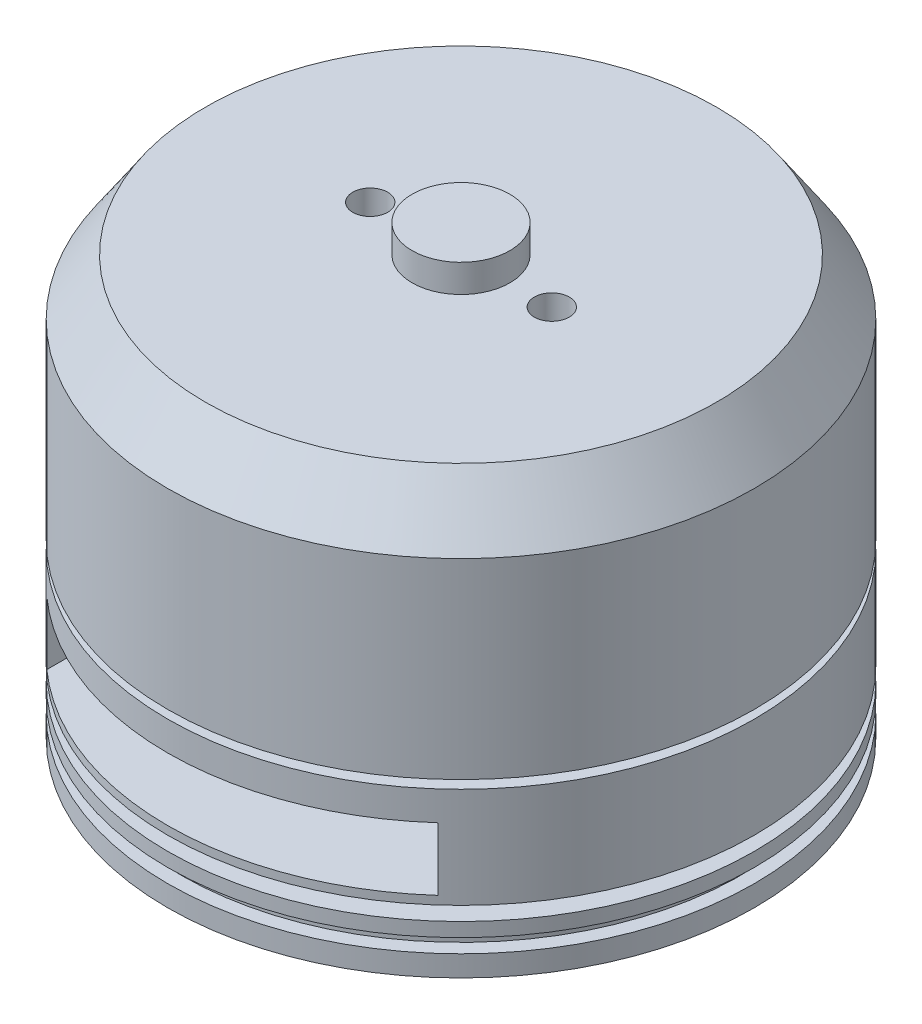
SolidWorks part; units mm, degrees
ref_plane "前视基准面" through (0, 0, 0) normal (0, 0, 1) x (1, 0, 0)
ref_plane "上视基准面" through (0, 0, 0) normal (0, 1, 0) x (1, 0, 0)
ref_plane "右视基准面" through (0, 0, 0) normal (1, 0, 0) x (0, 0, -1)
sketch "草图1" plane through (0, 0, 0) normal (0, 0, 1) x (1, 0, 0)
  line L0 (0, 0) -> (4.1, 0)
  line L1 (4.1, 0) -> (4.1, 6.7)
  line L2 (4.1, 6.7) -> (13.4, 6.7)
  line L3 (13.4, 6.7) -> (13.4, 8.7)
  line L4 (13.4, 8.7) -> (21, 8.7)
  line L5 (21, 8.7) -> (21, 10.2)
  line L6 (21, 10.2) -> (20, 10.2)
  line L7 (20, 10.2) -> (20, 11.2)
  line L8 (20, 11.2) -> (21, 11.2)
  line L9 (21, 11.2) -> (21, 12.2)
  line L10 (21, 12.2) -> (10, 12.2)
  line L11 (10, 12.2) -> (10, 13.2)
  line L12 (10, 13.2) -> (21, 13.2)
  line L13 (21, 13.2) -> (21, 20.4)
  line L14 (21, 20.4) -> (5, 20.4)
  line L15 (5, 20.4) -> (5, 21)
  line L16 (5, 21) -> (21, 21)
  line L17 (21, 21) -> (21, 34.7)
  line L18 (21, 34.7) -> (18.3, 38.7)
  line L19 (18.3, 38.7) -> (3.5, 38.7)
  line L20 (3.5, 38.7) -> (3.5, 43.7)
  line L21 (3.5, 43.7) -> (0, 43.7)
  line L22 (0, 43.7) -> (0, 0) construction
  line L23 (0, 0) -> (0, 43.7)
  dimension "D1" = 8.2
  dimension "D2" = 26.8
  dimension "D3" = 42
  dimension "D4" = 10
  dimension "D5" = 1.5
  dimension "D6" = 1
  dimension "D7" = 1
  dimension "D8" = 20
  dimension "D9" = 1
  dimension "D10" = 7.2
  dimension "D11" = 0.6
  dimension "D12" = 13.7
  dimension "D13" = 5
  dimension "D14" = 2
  dimension "D15" = 6.7
  dimension "D16" = 1
  dimension "D17" = 7
  dimension "D18" = 36.6
  dimension "D19" = 4
  dimension "D20" = 30
revolve "旋转1" add sketch "草图1" angle 360 about L22
ref_plane "基准面1" through (0, 0, 21) normal (0, 0, 1) x (1, 0, 0)
sketch "草图2" plane through (0, 0, 21) normal (0, 0, 1) x (1, 0, 0)
  line L1 (-14, 18.3) -> (14, 18.3)
  line L2 (-14, 18.3) -> (-14, 13.8)
  line L3 (-14, 13.8) -> (14, 13.8)
  line L4 (14, 18.3) -> (14, 13.8)
  line L5 (-14, 18.3) -> (14, 13.8) construction
  line L6 (-14, 13.8) -> (14, 18.3) construction
  line L7 (-21, 13.2) -> (21, 13.2) construction
  point P0 (0, 16.05)
  dimension "D1" = 28
  dimension "D2" = 4.5
  dimension "D3" = 0.6
extrude "切除-拉伸1" cut sketch "草图2" against normal blind 10
hole_wizard "M3 螺纹孔1" positions "草图5" profile "草图6" tap size "M3" standard "GB"
sketch "草图5" plane through (0, 38.7, 0) normal (0, 1, 0) x (1, 0, 0)
  line L0 (0, 0) -> (0, 8.0606) construction
  point P0 (-6.5, 0)
  point P2 (6.5, 0)
  dimension "D1" = 13
sketch "草图6" plane through (-6.5, 38.7, 0) normal (1, 0, 0) x (0, 0, 1)
  line L0 (0, 0) -> (0, 4.7511)
  line L1 (0, 4.7511) -> (1.25, 4)
  line L2 (1.25, 4) -> (1.25, 0)
  line L5 (1.25, 0) -> (0, 0)
  line L10 (0, 4.7511) -> (-1.25, 4) construction
  line L11 (0, -6.35) -> (0, 107.95) construction
  dimension "螺纹孔钻头直径" = 2.5
  dimension "螺纹孔钻头深度" = 4
  dimension "导头角度" = 118
cosmetic thread "孔螺蚊线1" parameters "D1"=4, "D2"=3
cosmetic thread "孔螺蚊线2" parameters "D1"=4, "D2"=3
sketch "草图18" plane through (0, 43.7, 0) normal (0, 1, 0) x (1, 0, 0)
  circle A0 centre (0, 0) radius 3.5
extrude "切除-拉伸3" cut sketch "草图18" against normal blind 3
sketch "草图7" plane through (0, 0, 0) normal (0, 0, 1) x (1, 0, 0)
  line L0 (0, 8.7) -> (0, -54.6) construction
  line L1 (-13.4, 8.7) -> (13.4, 8.7) construction
  line L2 (0, -54.6) -> (5, -54.6)
  line L3 (5, -54.6) -> (5, -30.5)
  line L4 (5, -30.5) -> (8.275, -30.5)
  line L5 (13, -29.6) -> (13, -27.6)
  line L6 (13, -27.6) -> (21, -27.6)
  line L7 (21, -27.6) -> (21, 8.7)
  line L8 (-21, 8.7) -> (21, 8.7) construction
  line L9 (21, 8.7) -> (0, 8.7)
  line L10 (18.3, 38.7) -> (-18.3, 38.7) construction
  line L11 (13, -29.6) -> (8.275, -29.6)
  line L12 (8.275, -29.6) -> (8.275, -30.5)
  line L13 (0, 8.7) -> (0, -54.6)
  dimension "D1" = 66.3
  dimension "D2" = 2
  dimension "D3" = 0.9
  dimension "D4" = 27
  dimension "D5" = 26
  dimension "D6" = 10
  dimension "D7" = 16.55
sketch "草图19" plane through (0, 0, 0) normal (0, -1, 0) x (1, 0, 0)
  circle A0 centre (0, 0) radius 4.1
extrude "切除-拉伸4" cut sketch "草图19" against normal up to surface (6.7 mm away) up to face at (0, 6.7, 13.4)
